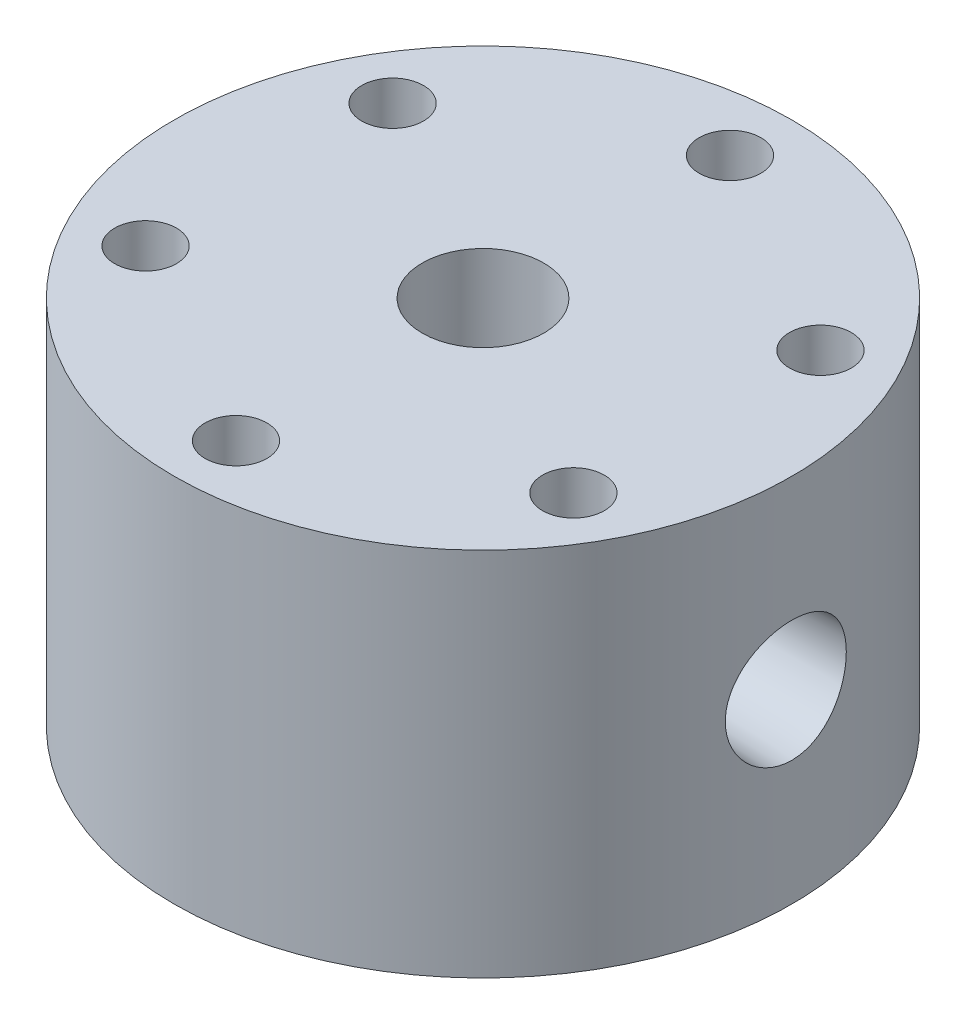
SolidWorks part; units mm, degrees
ref_plane "Front Plane" through (0, 0, 0) normal (0, 0, 1) x (1, 0, 0)
ref_plane "Top Plane" through (0, 0, 0) normal (0, 1, 0) x (1, 0, 0)
ref_plane "Right Plane" through (0, 0, 0) normal (1, 0, 0) x (0, 0, -1)
sketch "Sketch1" plane through (0, 0, 0) normal (0, 0, 1) x (1, 0, 0)
  line L2 (-12.7, 0) -> (-31.75, 0)
  line L3 (-31.75, 0) -> (-31.75, 38.1)
  line L4 (-31.75, 38.1) -> (-3.81, 38.1)
  line L6 (-3.81, 38.1) -> (-3.81, 6.35)
  line L10 (0, 0) -> (0, 15.7692) construction
  line L11 (-11.1125, 6.35) -> (-12.7, 6.35)
  line L12 (-12.7, 6.35) -> (-12.7, 0)
  line L13 (-3.81, 6.35) -> (-8.0645, 6.35)
  line L14 (-8.0645, 6.35) -> (-8.0645, 8.382)
  line L15 (-8.0645, 8.382) -> (-11.1125, 8.382)
  line L16 (-11.1125, 8.382) -> (-11.1125, 6.35)
  dimension "D1" = 3.81
  dimension "D2" = 12.7
  dimension "D3" = 6.35
  dimension "D4" = 38.1
  dimension "D5" = 31.75
  dimension "D6" = 3.048
  dimension "D7" = 2.032
  dimension "D8" = 1.5875
revolve "Revolve1" add sketch "Sketch1" angle 360 about L10
hole_wizard "M14x1.5 Tapped Hole1" positions "Sketch2" profile "Sketch4" tap size "M14x1.5" standard "ANSI Metric"
sketch "Sketch2" plane through (0, 38.1, 0) normal (0, 1, 0) x (1, 0, 0)
  point P0 (0, 0)
sketch "Sketch4" plane through (0, 38.1, 0) normal (1, 0, 0) x (0, 0, 1)
  line L0 (0, 0) -> (0, 29.1554)
  line L1 (0, 29.1554) -> (6.25, 25.4)
  line L2 (6.25, 25.4) -> (6.25, 0)
  line L5 (6.25, 0) -> (0, 0)
  line L10 (0, 29.1554) -> (-6.25, 25.4) construction
  line L11 (0, -6.35) -> (0, 107.95) construction
  dimension "Tap Drill Dia." = 12.5
  dimension "Tap Drill Depth" = 25.4
  dimension "Drill Angle" = 118
cosmetic thread "Hole Thread3"
ref_plane "Plane1" through (31.75, 0, 0) normal (1, 0, 0) x (0, 0, -1)
ref_plane "Plane2" through (-31.75, 0, 0) normal (-1, 0, 0) x (0, 0, 1)
hole_wizard "1/4 NPT Tapped Hole1" positions "Sketch5" profile "Sketch6" size "1/4" standard "ANSI Inch"
sketch "Sketch5" plane through (31.75, 0, 0) normal (1, 0, 0) x (0, 0, -1)
  line L0 (31.75, 38.1) -> (-31.75, 38.1) construction
  point P0 (0, 19.05)
  dimension "D1" = 19.05
sketch "Sketch6" plane through (31.75, 19.05, 0) normal (0, 1, 0) x (0, 0, -1)
  line L0 (0, 0) -> (0, 20.3603)
  line L1 (5.5626, 17.018) -> (0, 20.3603)
  line L2 (-5.5626, 17.018) -> (0, 20.3603) construction
  line L3 (5.5626, 17.018) -> (5.5626, 9.906)
  line L4 (5.5626, 9.906) -> (5.9437, 9.906)
  line L5 (5.9437, 9.906) -> (6.2403, 0)
  line L6 (-5.9437, 9.906) -> (-6.2403, 0) construction
  line L7 (6.2403, 0) -> (0, 0)
  line L8 (0, -6.35) -> (0, 107.95) construction
  line L11 (-5.5626, 9.906) -> (-5.9437, 9.906) construction
  dimension "Tap Drill Dia." = 11.1252
  dimension "Tap Drill Depth" = 17.018
  dimension "Thread Dia." = 12.4806
  dimension "Thread Angle" = 3.43
  dimension "Thread Depth" = 9.906
  dimension "Drill Angle" = 118
cosmetic thread "Hole Thread1"
hole_wizard "1/4 NPT Tapped Hole2" positions "Sketch7" profile "Sketch8" size "1/4" standard "ANSI Inch"
sketch "Sketch7" plane through (-31.75, 0, 0) normal (-1, 0, 0) x (0, 0, 1)
  line L0 (31.75, 38.1) -> (-31.75, 38.1) construction
  point P0 (0, 19.05)
  dimension "D1" = 19.05
sketch "Sketch8" plane through (-31.75, 19.05, 0) normal (0, 1, 0) x (0, 0, 1)
  line L0 (0, 0) -> (0, 20.3603)
  line L1 (5.5626, 17.018) -> (0, 20.3603)
  line L2 (-5.5626, 17.018) -> (0, 20.3603) construction
  line L3 (5.5626, 17.018) -> (5.5626, 9.906)
  line L4 (5.5626, 9.906) -> (5.9437, 9.906)
  line L5 (5.9437, 9.906) -> (6.2403, 0)
  line L6 (-5.9437, 9.906) -> (-6.2403, 0) construction
  line L7 (6.2403, 0) -> (0, 0)
  line L8 (0, -6.35) -> (0, 107.95) construction
  line L11 (-5.5626, 9.906) -> (-5.9437, 9.906) construction
  dimension "Tap Drill Dia." = 11.1252
  dimension "Tap Drill Depth" = 17.018
  dimension "Thread Dia." = 12.4806
  dimension "Thread Angle" = 3.43
  dimension "Thread Depth" = 9.906
  dimension "Drill Angle" = 118
cosmetic thread "Hole Thread2" parameters "D1"=9.906, "D2"=13.7086
hole_wizard "1/16 (0.0625) Diameter Hole1" positions "Sketch9" profile "Sketch10" hole size "1/16" standard "ANSI Inch"
sketch "Sketch9" plane through (31.75, 0, 0) normal (1, 0, 0) x (0, 0, -1)
  point P0 (0, 19.05)
sketch "Sketch10" plane through (31.75, 19.05, 0) normal (0, 1, 0) x (0, 0, -1)
  line L0 (0, 0) -> (0, 29.0519)
  line L1 (0, 29.0519) -> (0.7937, 28.575)
  line L2 (0.7937, 28.575) -> (0.7937, 0)
  line L5 (0.7937, 0) -> (0, 0)
  line L10 (0, 29.0519) -> (-0.7938, 28.575) construction
  line L11 (0, -6.35) -> (0, 107.95) construction
  dimension "Hole Dia." = 1.5875
  dimension "Hole Depth" = 28.575
  dimension "Drill Angle" = 118
hole_wizard "3/32 (0.09375) Diameter Hole1" positions "Sketch11" profile "Sketch12" hole size "3/32" standard "ANSI Inch"
sketch "Sketch11" plane through (-31.75, 0, 0) normal (-1, 0, 0) x (0, 0, 1)
  point P0 (0, 19.05)
sketch "Sketch12" plane through (-31.75, 19.05, 0) normal (0, 1, 0) x (0, 0, 1)
  line L0 (0, 0) -> (0, 29.4174)
  line L1 (0, 29.4174) -> (1.1906, 28.702)
  line L2 (1.1906, 28.702) -> (1.1906, 0)
  line L5 (1.1906, 0) -> (0, 0)
  line L10 (0, 29.4174) -> (-1.1906, 28.702) construction
  line L11 (0, -6.35) -> (0, 107.95) construction
  dimension "Hole Dia." = 2.3812
  dimension "Hole Depth" = 28.702
  dimension "Drill Angle" = 118
hole_wizard "1/4 (0.25) Diameter Hole1" positions "Sketch15" profile "Sketch16" hole size "1/4" standard "ANSI Inch" end condition through all
sketch "Sketch15" plane through (0, 38.1, 0) normal (0, 1, 0) x (1, 0, 0)
  line L0 (0, 0) -> (16.0984, 0) construction
  line L2 (0, 0) -> (21.997, 12.7) construction
  point P0 (21.997, 12.7)
  dimension "D1" = 25.4
  dimension "D2" = 30
sketch "Sketch16" plane through (21.997, 38.1, -12.7) normal (1, 0, 0) x (0, 0, 1)
  line L0 (0, 0) -> (0, 38.1)
  line L1 (0, 38.1) -> (3.175, 38.1)
  line L2 (3.175, 38.1) -> (3.175, 0)
  line L5 (3.175, 0) -> (0, 0)
  line L11 (0, -6.35) -> (0, 107.95) construction
  dimension "Thru Hole Dia." = 6.35
  dimension "Thru Hole Depth" = 38.1
pattern_circular "CirPattern1" count 6 over 360 about axis through (0, 0, 0) along (0, 1, 0) of "1/4 (0.25) Diameter Hole1"
ref_plane "Plane3" through (15.875, 0, -27.4963) normal (0.5, 0, -0.866) x (0, -1, 0)
hole_wizard "1/4 NPT Tapped Hole3" positions "Sketch17" profile "Sketch18" size "1/4" standard "ANSI Inch"
sketch "Sketch17" plane through (15.875, 0, -27.4963) normal (0.5, 0, -0.866) x (0, -1, 0)
  point P0 (-19.05, 0)
  point P3 (-19.05, 0)
  point P6 (-16.6975, 0)
  dimension "D1" = 19.05
sketch "Sketch18" plane through (15.875, 19.05, -27.4963) normal (0, 1, 0) x (-0.866, 0, -0.5)
  line L0 (0, 0) -> (0, 20.3603)
  line L1 (5.5626, 17.018) -> (0, 20.3603)
  line L2 (-5.5626, 17.018) -> (0, 20.3603) construction
  line L3 (5.5626, 17.018) -> (5.5626, 9.906)
  line L4 (5.5626, 9.906) -> (5.9437, 9.906)
  line L5 (5.9437, 9.906) -> (6.2403, 0)
  line L6 (-5.9437, 9.906) -> (-6.2403, 0) construction
  line L7 (6.2403, 0) -> (0, 0)
  line L8 (0, -6.35) -> (0, 107.95) construction
  line L11 (-5.5626, 9.906) -> (-5.9437, 9.906) construction
  dimension "Tap Drill Dia." = 11.1252
  dimension "Tap Drill Depth" = 17.018
  dimension "Thread Dia." = 12.4806
  dimension "Thread Angle" = 3.43
  dimension "Thread Depth" = 9.906
  dimension "Drill Angle" = 118
cosmetic thread "Hole Thread5"
hole_wizard "1/32 (0.03125) Diameter Hole1" positions "Sketch21" profile "Sketch22" hole size "1/32" standard "ANSI Inch"
sketch "Sketch21" plane through (15.875, 0, -27.4963) normal (0.5, 0, -0.866) x (0, -1, 0)
  point P0 (-19.05, 0)
sketch "Sketch22" plane through (15.875, 19.05, -27.4963) normal (0, 1, 0) x (-0.866, 0, -0.5)
  line L0 (0, 0) -> (0, 28.8135)
  line L1 (0, 28.8135) -> (0.3969, 28.575)
  line L2 (0.3969, 28.575) -> (0.3969, 0)
  line L5 (0.3969, 0) -> (0, 0)
  line L10 (0, 28.8135) -> (-0.3969, 28.575) construction
  line L11 (0, -6.35) -> (0, 107.95) construction
  dimension "Hole Dia." = 0.7937
  dimension "Hole Depth" = 28.575
  dimension "Drill Angle" = 118
